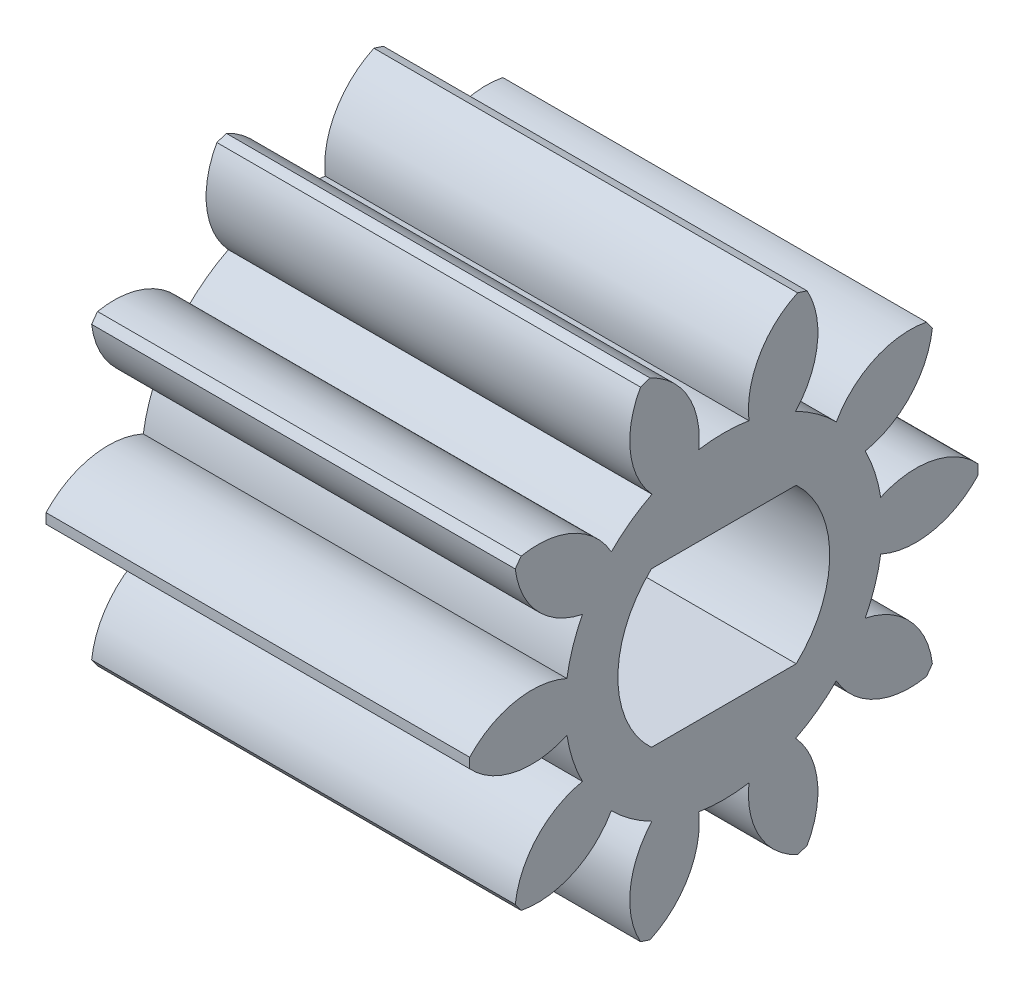
SolidWorks part; units mm, degrees
ref_plane "Plane1" through (0, 0, 0) normal (0, 0, 1) x (1, 0, 0)
ref_plane "Plane2" through (0, 0, 0) normal (0, 1, 0) x (1, 0, 0)
ref_plane "Plane3" through (0, 0, 0) normal (1, 0, 0) x (0, 0, -1)
sketch "HoldingSke" plane through (0, 0, 0) normal (0, 1, 0) x (1, 0, 0)
  line L0 (0, 0) -> (0.9848, -0.1736)
  line L1 (-15, 0) -> (100, 0) construction
  line L2 (0, 0) -> (-2.1039, 2.3779)
  line L3 (0, 0) -> (-11.863, 4.5341)
  line L4 (0, 0) -> (8.5048, 1.4996)
  line L5 (0, 0) -> (-46.8476, -17.4728)
  line L6 (0, 0) -> (-9.9476, -6.7116)
  line L7 (-2.1039, 2.3779) -> (8.6586, 51.2059)
  line L8 (-76.2, 54.61) -> (-76.1, 54.61)
  line L9 (-71.009, 38.7566) -> (-53.1078, 45.2721)
  line L10 (-76.2, 71.12) -> (104.1128, 71.12)
  line L11 (0, 0) -> (-12, 0)
  line L12 (-76.2, 101.6) -> (-76.162, 101.6)
  line L13 (24.9733, 27.94) -> (52.9518, 28.4284)
  line L14 (24.9733, 27.94) -> (24.9743, 27.94)
  line L15 (24.9733, 27.94) -> (100.4006, 29.5858)
  line L16 (-63.627, -1) -> (-12.827, -1)
  circle A0 centre (0, 0) radius 0.4
  circle A1 centre (0, 0) radius 3.749
  circle A2 centre (0, 0) radius 37.5
  circle A3 centre (0, 0) radius 0.4
  dimension "MHD" = 7.498
  dimension "Hub_dia" = 75
  dimension "Bore" = 0.8
  dimension "MBD" = 0.8
  dimension "Num_teeth" = 10
  dimension "Pitch" = 1
  dimension "Overall_len" = 50
  dimension "Show_teeth" = 10
  dimension "Thickness" = 12
  dimension "OAL" = 50.0001
  dimension "T_dim" = 0.1
  dimension "Ap" = 20
  dimension "H" = 19.05
  dimension "Pitch_radius" = 180.3128
  dimension "Width" = 12
  dimension "Backlash" = 0.038
  dimension "Addendum_fac" = 1
  dimension "Dedendum_fac" = 1.25
  dimension "Clearance_fac" = 0.25
  dimension "Dedendum_add" = 0.001
  dimension "Module" = 1
sketch "BasProSke" plane through (0, 0, 0) normal (0, 1, 0) x (1, 0, 0)
  line L0 (-10, 0) -> (60, 0) construction
  line L1 (0, 0) -> (0, 6)
  line L2 (0, 0) -> (10, 0)
  line L3 (10, 0) -> (10, 6)
  line L4 (10, 6) -> (0, 6)
  dimension "Thickness" = 10
  dimension "Diameter" = 12
revolve "Base-Revolve" add sketch "BasProSke" angle 360 about L0
sketch "TooCutSke" plane through (0, 0, 0) normal (1, 0, 0) x (0, 0, -1)
  line L1 (0, 0) -> (0, 107) construction
  line L2 (0, 0) -> (-0.8485, 4.9275) construction
  line L3 (0, 0) -> (-3.0584, 9.4126) construction
  line L4 (-0.8485, 4.9275) -> (-1.5292, 4.7063) construction
  arc A0 (0.5928, 3.7018) -> (-0.5928, 3.7018) centre (0, 0) ccw
  arc A1 (1.7758, 5.7578) -> (-1.7758, 5.7578) centre (0, 0) ccw
  circle A2 centre (0, 0) radius 5 construction
  circle A3 centre (0, 0) radius 4.6985 construction
  arc A4 (-0.5928, 3.7018) -> (-1.7758, 5.7578) centre (-2.5801, 3.9267) ccw
  arc A5 (1.7758, 5.7578) -> (0.5928, 3.7018) centre (2.5801, 3.9267) ccw
  dimension "Root_dia" = 7.498
  dimension "Overcut_dia" = 12.0508
  dimension "Pitch_dia" = 10
  dimension "Base_dia" = 9.3969
  dimension "Flank_rad" = 2
  dimension "Half_ang" = 18
  dimension "Half_CT" = 0.7157
extrude "ToothCut" cut sketch "TooCutSke" along normal through all
fillet "Breaks" [suppressed] radius 0.02
fillet "RootFillets" [suppressed] radius 0.251
pattern_circular "TeethCuts" count 10 every 36 about axis through (-10, 0, 0) along (1, 0, 0) of "ToothCut", "RootFillets", "Breaks"
sketch "HubNeaOneSke" plane through (0, 0, 0) normal (-1, 0, 0) x (0, 0, 1)
  circle A0 centre (0, 0) radius 3.749
  dimension "Diameter" = 7.498
extrude "HubNearOne" [suppressed] add sketch "HubNeaOneSke" along normal blind 40.0001
sketch "HubNeaBotSke" plane through (0, 0, 0) normal (-1, 0, 0) x (0, 0, 1)
  circle A0 centre (0, 0) radius 3.749
  dimension "Diameter" = 7.498
extrude "HubNearBoth" [suppressed] add sketch "HubNeaBotSke" along normal blind 20
ref_plane "FarPln" through (10, 0, 0) normal (1, 0, 0) x (0, 0, -1)
sketch "HubFarSke" plane through (10, 0, 0) normal (1, 0, 0) x (0, 0, -1)
  circle A0 centre (0, 0) radius 3.749
  dimension "Diameter" = 7.498
extrude "HubFar" [suppressed] add sketch "HubFarSke" along normal blind 20
sketch "BorSke" plane through (0, 0, 0) normal (1, 0, 0) x (0, 0, -1)
  circle A0 centre (0, 0) radius 0.4
  dimension "Diameter" = 0.8
extrude "Bore" cut sketch "BorSke" along normal mid plane 100.0001
sketch "KeySke" plane through (0, 0, 0) normal (1, 0, 0) x (0, 0, -1)
  line L0 (-0.05, 0) -> (-0.05, 0.5)
  line L1 (-0.05, 0.5) -> (0.05, 0.5)
  line L2 (0.05, 0.5) -> (0.05, 0)
  line L3 (0, 0) -> (0, 34) construction
  line L4 (-0.05, 0) -> (0.05, 0)
  dimension "Offset" = 0.5
  dimension "Width" = 0.1
extrude "Keyway" [suppressed] cut sketch "KeySke" along normal mid plane 100.0001
pattern_circular "Keyway2" [suppressed] count 2 every 90 about axis through (-10, 0, 0) along (1, 0, 0)
sketch "Sketch1" plane through (10, 0, 0) normal (1, 0, 0) x (0, 0, -1)
  line L1 (-3.2877, -1.825) -> (3.2877, -1.825)
  line L2 (-3.2877, -1.825) -> (-3.2877, 1.825)
  line L3 (-3.2877, 1.825) -> (3.2877, 1.825)
  line L4 (3.2877, -1.825) -> (3.2877, 1.825)
  line L5 (-3.2877, -1.825) -> (3.2877, 1.825) construction
  line L6 (-3.2877, 1.825) -> (3.2877, -1.825) construction
  circle A0 centre (0, 0) radius 2.5
  circle A1 centre (0, 0) radius 4.8745 construction
  circle M2 centre (0, 0) radius 0.4
  dimension "D1" = 5
  dimension "D2" = 9.749
  dimension "D3" = 3.65
extrude "Cut-Extrude1" cut sketch "Sketch1" against normal through all contours L3 A0 L1 M2
sketch "Sketch2" plane through (10, 0, 0) normal (1, 0, 0) x (0, 0, -1)
  circle A0 centre (0, 0) radius 4.8745 construction
  dimension "D1" = 9.749
equation "' \"Module@HoldingSke\" = 6.35"
equation "' \"Num_teeth@HoldingSke\" = 12"
equation "' \"Ap@HoldingSke\" =  20"
equation "' \"Ap@HoldingSke\" = 20"
equation "' \"Width@HoldingSke\" = 0.5 * 25.4"
equation "' \"Hub_dia@HoldingSke\"= 1 * 25.4"
equation "' \"Hub_dia@HoldingSke\" = 1 * 25.4"
equation "' \"Overall_len@HoldingSke\" = 1.0 * 25.4"
equation "' \"Bore@HoldingSke\" = 0.75 * 25.4"
equation "' \"T_dim@HoldingSke\" = 0.1 * 25.4"
equation "' \"Width@KeySke\" = 0.25 * 25.4"
equation "' \"Show_teeth@HoldingSke\" = 13"
equation "' \"Backlash@HoldingSke\" = 0.009 * 25.4"
equation "' \"Addendum_fac@HoldingSke\" = 1.0"
equation "' \"Dedendum_fac@HoldingSke\" = 1.25"
equation "' \"Dedendum_add@HoldingSke\" = 0.00005 * 25.4"
equation "' \"Clearance_fac@HoldingSke\" = 0.25"
equation "\"Pitch@HoldingSke\" = 1 / \"Module@HoldingSke\""
equation "\"Overcut_dia@TooCutSke\" = (\"Num_teeth@HoldingSke\" + 2 * \"Addendum_fac@HoldingSke\") / \"Pitch@HoldingSke\" + 0.002 * 25.4"
equation "\"Pitch_dia@TooCutSke\" = \"Num_teeth@HoldingSke\" / \"Pitch@HoldingSke\""
equation "\"Base_dia@TooCutSke\" = \"Num_teeth@HoldingSke\" / \"Pitch@HoldingSke\" * cos((\"Ap@HoldingSke\"  * 3.14159265 / 180))"
equation "\"Root_dia@TooCutSke\" = (\"Num_teeth@HoldingSke\" + 2) / \"Pitch@HoldingSke\" - 2 * (\"Addendum_fac@HoldingSke\" + \"Dedendum_fac@HoldingSke\") / \"Pitch@HoldingSke\" - \"Dedendum_add@HoldingSke\" * 2"
equation "\"Half_ang@TooCutSke\" = 180 / \"Num_teeth@HoldingSke\""
equation "\"Half_CT@TooCutSke\" = \"Num_teeth@HoldingSke\" / \"Pitch@HoldingSke\" * sin((3.14159265 / 2 / \"Num_teeth@HoldingSke\")) / 2 - 7 * \"Backlash@HoldingSke\" / 4"
equation "\"Flank_rad@TooCutSke\" = \"Num_teeth@HoldingSke\" / \"Pitch@HoldingSke\" / 5"
equation "\"Radius@RootFillets\" = \"Clearance_fac@HoldingSke\" / \"Pitch@HoldingSke\" + \"Dedendum_add@HoldingSke\""
equation "\"Break_rad@Breaks\" = 0.02 / \"Pitch@HoldingSke\""
equation "\"Thickness@HoldingSke\" = \"Width@HoldingSke\""
equation "\"OAL@HoldingSke\" = \"Thickness@HoldingSke\""
equation "\"MHD@HoldingSke\" = (\"Num_teeth@HoldingSke\" + 2) / \"Pitch@HoldingSke\" - 2 * (\"Addendum_fac@HoldingSke\" + \"Dedendum_fac@HoldingSke\")  / \"Pitch@HoldingSke\" - \"Dedendum_add@HoldingSke\" * 2"
equation "\"MBD@HoldingSke\" = (\"Num_teeth@HoldingSke\" + 2) / \"Pitch@HoldingSke\" - 2 * (\"Addendum_fac@HoldingSke\" + \"Dedendum_fac@HoldingSke\")  / \"Pitch@HoldingSke\" - \"Dedendum_add@HoldingSke\" * 2 - 0.002 * 25.4"
equation "\"MHD@HoldingSke\" = ((sgn( \"MHD@HoldingSke\" - \"Hub_dia@HoldingSke\" )-1)*( \"MHD@HoldingSke\" - \"Hub_dia@HoldingSke\" ))/-2+ \"Hub_dia@HoldingSke\""
equation "\"MBD@HoldingSke\" = ((sgn( \"MBD@HoldingSke\" - \"Bore@HoldingSke\" )-1)*( \"MBD@HoldingSke\" - \"Bore@HoldingSke\" ))/-2+ \"Bore@HoldingSke\""
equation "\"OAL@HoldingSke\" = ((sgn( \"OAL@HoldingSke\" - \"Overall_len@HoldingSke\" )+1)*( \"OAL@HoldingSke\" - \"Overall_len@HoldingSke\" ))/2 + \"Overall_len@HoldingSke\" + 0.000002 * 25.4"
equation "\"Num_teeth@TeethCuts\" = int( \"Show_teeth@HoldingSke\" ) + 1"
equation "\"Num_teeth@TeethCuts\" = ((sgn( \"Num_teeth@TeethCuts\" - \"Num_teeth@HoldingSke\" )-1)*( \"Num_teeth@TeethCuts\" - \"Num_teeth@HoldingSke\" ))/-2+ \"Num_teeth@HoldingSke\""
equation "\"Num_teeth@TeethCuts\" = ((sgn( \"Num_teeth@TeethCuts\" - 2.0)+1)*( \"Num_teeth@TeethCuts\" - 2.0))/2 +2.0"
equation "\"Angle@TeethCuts\" = 360.0 / \"Num_teeth@HoldingSke\""
equation "\"Diameter@BasProSke\" = (\"Num_teeth@HoldingSke\" + 2 * \"Addendum_fac@HoldingSke\") / \"Pitch@HoldingSke\""
equation "' \"Fillet_rad@BasProSke\" =  \"Thickness@HoldingSke\" * 0.05"
equation "' \"Fillet_rad@BasProSke\" = \"Thickness@HoldingSke\" * 0.05"
equation "\"MHD@HoldingSke\" = ((sgn( \"MHD@HoldingSke\" - \"Root_dia@TooCutSke\" )-1)*( \"MHD@HoldingSke\" - \"Root_dia@TooCutSke\" ))/-2+ \"Root_dia@TooCutSke\""
equation "\"Diameter@HubNeaOneSke\" = \"MHD@HoldingSke\""
equation "\"Length@HubNearOne\" = \"OAL@HoldingSke\" - \"Thickness@BasProSke\""
equation "\"Diameter@HubNeaBotSke\" = \"MHD@HoldingSke\""
equation "\"Length@HubNearBoth\" = ( \"OAL@HoldingSke\" - \"Thickness@BasProSke\" ) / 2.0"
equation "\"Thickness@FarPln\" = \"Thickness@BasProSke\""
equation "\"Diameter@HubFarSke\" = \"MHD@HoldingSke\""
equation "\"Length@HubFar\" = ( \"OAL@HoldingSke\" - \"Thickness@BasProSke\" ) / 2.0"
equation "\"Diameter@BorSke\" = \"MBD@HoldingSke\""
equation "\"D1@Bore\" = \"OAL@HoldingSke\" * 2.0"
equation "\"D1@Keyway\" = \"OAL@HoldingSke\" * 2.0"
equation "\"Offset@KeySke\" = \"T_dim@HoldingSke\" + \"MBD@HoldingSke\" / 2.0"
